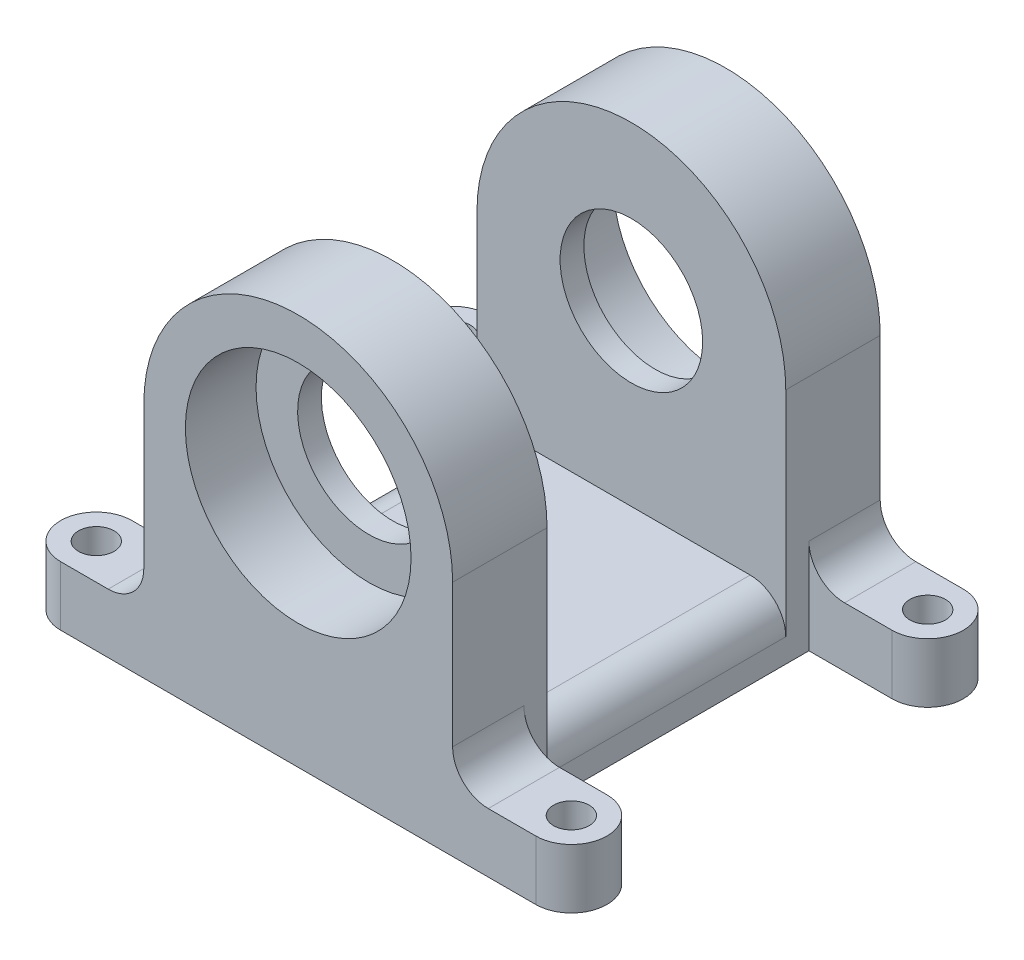
SolidWorks part; units mm, degrees
ref_plane "Alzado" through (0, 0, 0) normal (0, 0, 1) x (1, 0, 0)
ref_plane "Planta" through (0, 0, 0) normal (0, 1, 0) x (1, 0, 0)
ref_plane "Vista lateral" through (0, 0, 0) normal (1, 0, 0) x (0, 0, -1)
sketch "Croquis1" plane through (0, 0, 0) normal (0, 0, 1) x (1, 0, 0)
  line L0 (0, 0) -> (0, 17.6859) construction
  line L1 (0, 0) -> (-25.4426, 0) construction
  line L2 (-13, 0) -> (-13, -20)
  line L3 (-13, -20) -> (13, -20)
  line L4 (13, -20) -> (13, 0)
  circle A0 centre (0, 0) radius 9.5
  arc A1 (13, 0) -> (-13, 0) centre (0, 0) ccw
  dimension "D1" = 19
  dimension "D2" = 13
  dimension "D3" = 20
extrude "Saliente-Extruir1" add sketch "Croquis1" along normal blind 36
sketch "Croquis2" plane through (13, 0, 0) normal (1, 0, 0) x (0, 0, -1)
  line L0 (-18, -20) -> (-18, -29.3415) construction
  line L1 (-36, -20) -> (0, -20) construction
  line L4 (0, 13) -> (-36, 13) construction
  line L5 (-7.95, 13) -> (-28.05, 13)
  line L7 (-28.05, 13) -> (-28.05, -15)
  line L8 (-28.05, -15) -> (-7.95, -15)
  line L9 (-7.95, -15) -> (-7.95, 13)
  dimension "D1" = 20.1
  dimension "D2" = 5
extrude "Cortar-Extruir2" cut sketch "Croquis2" against normal through all
sketch "Croquis3" plane through (0, 0, 28.05) normal (0, 0, -1) x (-1, 0, 0)
  circle A0 centre (0, 0) radius 9.5
  circle A1 centre (0, 0) radius 6
  dimension "D1" = 19
  dimension "D2" = 12
extrude "Saliente-Extruir2" add sketch "Croquis3" against normal blind 2
sketch "Croquis4" plane through (0, 0, 7.95) normal (0, 0, 1) x (1, 0, 0)
  circle A0 centre (0, 0) radius 9.5 construction
  circle A1 centre (0, 0) radius 9.5
  circle A2 centre (0, 0) radius 6 construction
  circle A3 centre (0, 0) radius 6
extrude "Saliente-Extruir3" add sketch "Croquis4" against normal blind 2
sketch "Croquis5" plane through (0, -20, 0) normal (0, -1, 0) x (1, 0, 0)
  line L0 (13, 36) -> (20, 36)
  line L1 (20, 30) -> (13, 30)
  line L2 (13, 36) -> (13, 0) construction
  line L3 (13, 30) -> (13, 36)
  line L4 (13, 0) -> (20, 0)
  line L5 (20, 6) -> (13, 6)
  line L6 (13, 6) -> (13, 0)
  line L7 (0, 0) -> (0, -17.9347) construction
  line L8 (-13, 0) -> (-20, 0)
  line L9 (-20, 6) -> (-13, 6)
  line L10 (-13, 6) -> (-13, 0)
  line L11 (-13, 30) -> (-13, 36)
  line L12 (-13, 36) -> (-20, 36)
  line L13 (-20, 30) -> (-13, 30)
  arc A0 (20, 36) -> (20, 30) centre (20, 33) cw
  arc A1 (20, 0) -> (20, 6) centre (20, 3) ccw
  arc A2 (-20, 0) -> (-20, 6) centre (-20, 3) cw
  arc A3 (-20, 36) -> (-20, 30) centre (-20, 33) ccw
  dimension "D1" = 7
  dimension "D2" = 3
  dimension "D4" = 3
  dimension "D3" = 7
extrude "Saliente-Extruir4" add sketch "Croquis5" against normal blind 5
sketch "Croquis6" plane through (0, -20, 0) normal (0, -1, 0) x (1, 0, 0)
  circle A0 centre (-20, 33) radius 1.5
  circle A1 centre (20, 33) radius 1.5
  circle A2 centre (-20, 3) radius 1.5
  circle A3 centre (20, 3) radius 1.5
  dimension "D1" = 3
  dimension "D2" = 3
  dimension "D3" = 3
  dimension "D4" = 3
extrude "Cortar-Extruir3" cut sketch "Croquis6" against normal through all
fillet "Redondeo1" radius 3 4 edges at (-13, -15, 33) (-13, -15, 3) (13, -15, 3) (13, -15, 33)
fillet "Redondeo2" radius 3 2 edges at (-13, -15, 18) (13, -15, 18)
